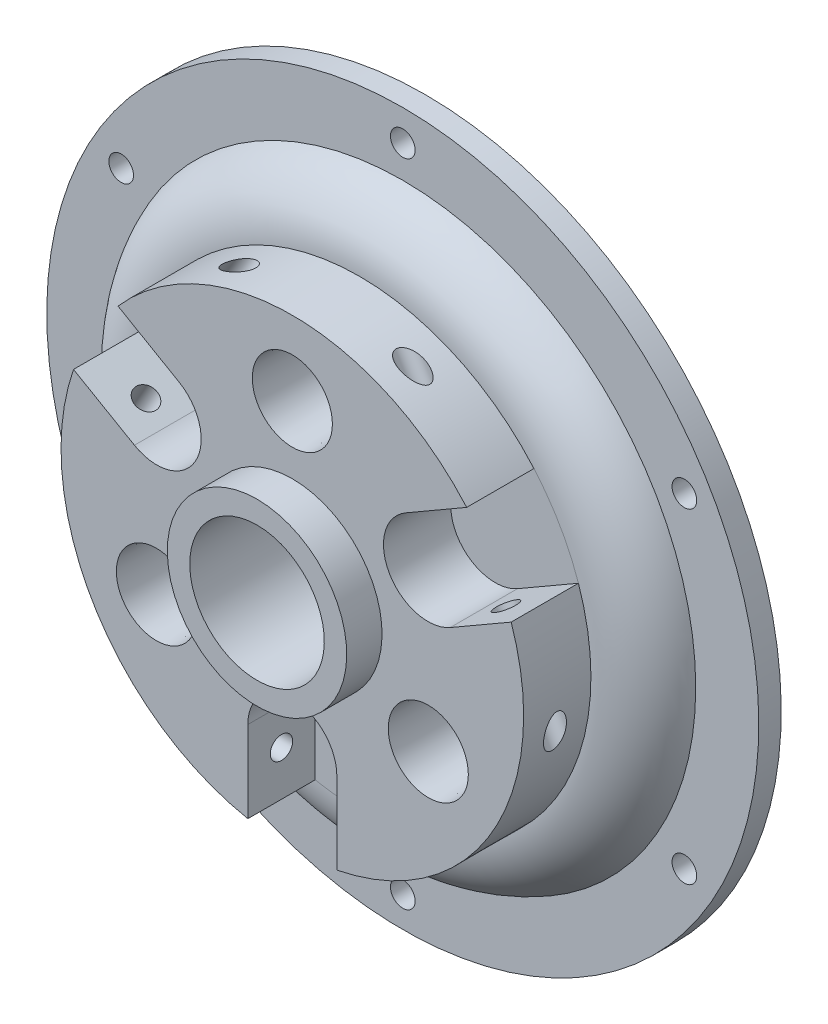
SolidWorks part; units mm, degrees
material "Copper"
ref_plane "Front Plane" through (0, 0, 0) normal (0, 0, 1) x (1, 0, 0)
ref_plane "Top Plane" through (0, 0, 0) normal (0, 1, 0) x (1, 0, 0)
ref_plane "Right Plane" through (0, 0, 0) normal (1, 0, 0) x (0, 0, -1)
ref_axis "CENTER" through (0, 0, 55) along (0, 0, -1)
sketch "Sketch1" plane through (0, 0, 0) normal (1, 0, 0) x (0, 0, -1)
  line L0 (0, 31.75) -> (0, 24.4792)
  line L2 (-3.85, 20.6292) -> (-3.85, 8)
  line L3 (-5.0047, 6) -> (-15, 6)
  line L4 (-15, 6) -> (-15, 8)
  line L5 (-2, 31.75) -> (0, 31.75)
  line L6 (128.0541, 0) -> (-49871.9459, 0) construction
  line L7 (-55, 0) -> (55, 0) construction
  line L8 (-2, 31.75) -> (-2, 26.1267)
  line L10 (-5.0047, 6) -> (-3.85, 8)
  line L12 (-11.85, 8) -> (-15, 8)
  line L14 (-5.85, 20.6292) -> (-11.85, 20.6292)
  line L15 (-11.85, 20.6292) -> (-11.85, 8)
  arc A0 (0, 24.4792) -> (-3.85, 20.6292) centre (0, 20.6292) ccw
  arc A1 (-2, 26.1267) -> (-5.85, 20.6292) centre (0, 20.6292) ccw
  dimension "D1" = 63.5
  dimension "D2" = 12
  dimension "D3" = 48.9584
  dimension "D4" = 2
  dimension "D5" = 2
  dimension "D6" = 3.85
  dimension "D7" = 15
  dimension "D8" = 30
  dimension "D9" = 2
  dimension "D11" = 2
  dimension "D14" = 8
revolve "Main Base" add sketch "Sketch1" angle 360 about L6
fillet "Tool Rad" [suppressed] radius 0.5
sketch "Fuel Ports" plane through (0, 0, 11.85) normal (0, 0, 1) x (1, 0, 0)
  circle A0 centre (0, 0) radius 14 construction
  point P3 (0, 14)
  point P4 (12.1244, -7)
  point P7 (-12.1244, -7)
  point P8 (0, 0)
  dimension "D1" = 28
  dimension "D2" = 3
hole_wizard "1/16 NPT Tapped Hole1" positions "Sketch3" profile "Sketch4" size "1/16" standard "ANSI Inch" end condition up to next
sketch "Sketch3" plane through (0, 0, 11.85) normal (0, 0, 1) x (1, 0, 0)
  point P0 (0, 14)
  point P3 (12.1244, -7)
  point P6 (-12.1244, -7)
sketch "Sketch4" plane through (0, 14, 11.85) normal (1, 0, 0) x (0, -1, 0)
  line L0 (0, 0) -> (0, 8)
  line L1 (0, 8) -> (3.0734, 8)
  line L2 (-3.3648, 6.89) -> (-3.5711, 0) construction
  line L3 (3.0734, 8) -> (3.0734, 6.89)
  line L4 (3.0734, 6.89) -> (3.3648, 6.89)
  line L5 (3.3648, 6.89) -> (3.5711, 0)
  line L7 (3.5711, 0) -> (0, 0)
  line L8 (0, -6.35) -> (0, 107.95) construction
  line L11 (-3.0734, 6.89) -> (-3.3648, 6.89) construction
  dimension "Thru Tap Drill Dia." = 6.1468
  dimension "Thru Tap Drill Depth" = 8
  dimension "Thread Dia." = 7.1422
  dimension "Thread Angle" = 3.43
  dimension "Thread Depth" = 6.89
cosmetic thread "Hole Thread1" parameters "D1"=6.89, "D2"=7.9374
cosmetic thread "Hole Thread2" parameters "D1"=6.89, "D2"=7.9374
cosmetic thread "Hole Thread3" parameters "D1"=6.89, "D2"=7.9374
sketch "Sketch5" plane through (0, 0, 11.85) normal (0, 0, 1) x (1, 0, 0)
  line L0 (0, 0) -> (17.8654, 10.3146) construction
  line L1 (0, 0) -> (50000, 0) construction
  line L2 (23.6335, 13.6448) -> (12.0973, 6.9844) construction
  line L3 (25.6179, 10.2078) -> (14.0817, 3.5473)
  line L4 (21.6491, 17.0818) -> (10.1129, 10.4214)
  line L5 (0, 0) -> (0, -20.6292) construction
  line L6 (0, 0) -> (-17.8654, 10.3146) construction
  line L7 (0, -28.2896) -> (0, -12.9688) construction
  line L8 (-3.9687, -28.2896) -> (-3.9687, -12.9688)
  line L9 (3.9688, -28.2896) -> (3.9688, -12.9688)
  line L10 (-23.6335, 13.6448) -> (-12.0973, 6.9844) construction
  line L11 (-21.6491, 17.0818) -> (-10.1129, 10.4214)
  line L12 (-25.6179, 10.2078) -> (-14.0817, 3.5473)
  circle A0 centre (0, 0) radius 20.6292 construction
  arc A1 (25.6179, 10.2078) -> (21.6491, 17.0818) centre (23.6335, 13.6448) ccw
  arc A2 (10.1129, 10.4214) -> (14.0817, 3.5473) centre (12.0973, 6.9844) ccw
  circle A3 centre (0, 0) radius 8 construction
  arc A4 (-3.9687, -28.2896) -> (3.9688, -28.2896) centre (0, -28.2896) ccw
  arc A5 (3.9688, -12.9688) -> (-3.9687, -12.9688) centre (0, -12.9688) ccw
  arc A6 (-21.6491, 17.0818) -> (-25.6179, 10.2078) centre (-23.6335, 13.6448) ccw
  arc A7 (-14.0817, 3.5473) -> (-10.1129, 10.4214) centre (-12.0973, 6.9844) ccw
  circle A8 centre (0, 0) radius 8 construction
  point P9 (17.8654, 10.3146)
  point P14 (8.6603, 5)
  point P16 (6.9282, 4)
  point P22 (0, 0)
  point P23 (0, -20.6292)
  point P29 (-17.8654, 10.3146)
  point P35 (-8.6603, 5)
  point P36 (0, -9)
  point P37 (-6.9282, 4)
  point P38 (0, -8)
  dimension "D1" = 30
  dimension "D2" = 7.9375
  dimension "D3" = 2
  dimension "D5" = 1
  dimension "D6" = 2
  dimension "D4" = 3
extrude "Thrust Mount" cut sketch "Sketch5" against normal offset from surface (6 mm away) 2 up to face at (0, 17.0734, 3.85)
sketch "Sketch6" plane through (0, 0, 0) normal (1, 0, 0) x (0, 0, -1)
  line L0 (-5.85, -16.2438) -> (-11.85, -16.2438) construction
  line L1 (-5.85, 6.6849) -> (-5.85, -20.2438) construction
  line L2 (-11.85, 6.6849) -> (-11.85, -20.2438) construction
  line L3 (-5.85, -20.2438) -> (-11.85, -20.2438) construction
  circle A0 centre (-8.85, -16.2438) radius 1
  point P8 (-8.85, -16.2438)
  dimension "D1" = 2
  dimension "D2" = 4
extrude "Locking Pin" cut sketch "Sketch6" against normal through all both and the other way through all
pattern_circular "CirPattern1" count 3 over 360 about axis through (0, 0, 55) along (0, 0, -1) of "Locking Pin"
sketch "Sketch7" plane through (0, 0, 0) normal (1, 0, 0) x (0, 0, -1)
  line L0 (0, -31.75) -> (0, 31.75) construction
  line L1 (0, 26.9792) -> (-0.5, 26.9792)
  line L2 (0, 26.9792) -> (0, 25.9792)
  line L3 (0, 25.9792) -> (-0.5, 25.9792)
  line L4 (-0.5, 26.9792) -> (-0.5, 25.9792)
  dimension "D1" = 0.5
  dimension "D2" = 1
  dimension "D3" = 1.5
revolve "Face O-ring" cut sketch "Sketch7" angle 360 about axis through (0, 0, 55) along (0, 0, -1)
sketch "Hole Pattern" plane through (0, 0, 0) normal (0, 0, 1) x (1, 0, 0)
  line L0 (0, 0) -> (0, 29) construction
  point P4 (0, 29)
  dimension "D1" = 29
hole_wizard "Ø2.2 (2.2) Diameter Hole1" positions "Sketch9" profile "Sketch10" hole size "Ø2.2" standard "ANSI Metric" end condition through all
sketch "Sketch9" plane through (0, 0, 2) normal (0, 0, 1) x (1, 0, 0)
  point P0 (0, 29)
sketch "Sketch10" plane through (0, 29, 2) normal (1, 0, 0) x (0, -1, 0)
  line L0 (0, 0) -> (0, 2)
  line L1 (0, 2) -> (1.1, 2)
  line L2 (1.1, 2) -> (1.1, 0)
  line L5 (1.1, 0) -> (0, 0)
  line L11 (0, -6.35) -> (0, 107.95) construction
  dimension "Thru Hole Dia." = 2.2
  dimension "Thru Hole Depth" = 2
pattern_circular "CirPattern2" count 6 over 360 about axis through (0, 0, 0) along (0, 0, 1) of "Ø2.2 (2.2) Diameter Hole1"
